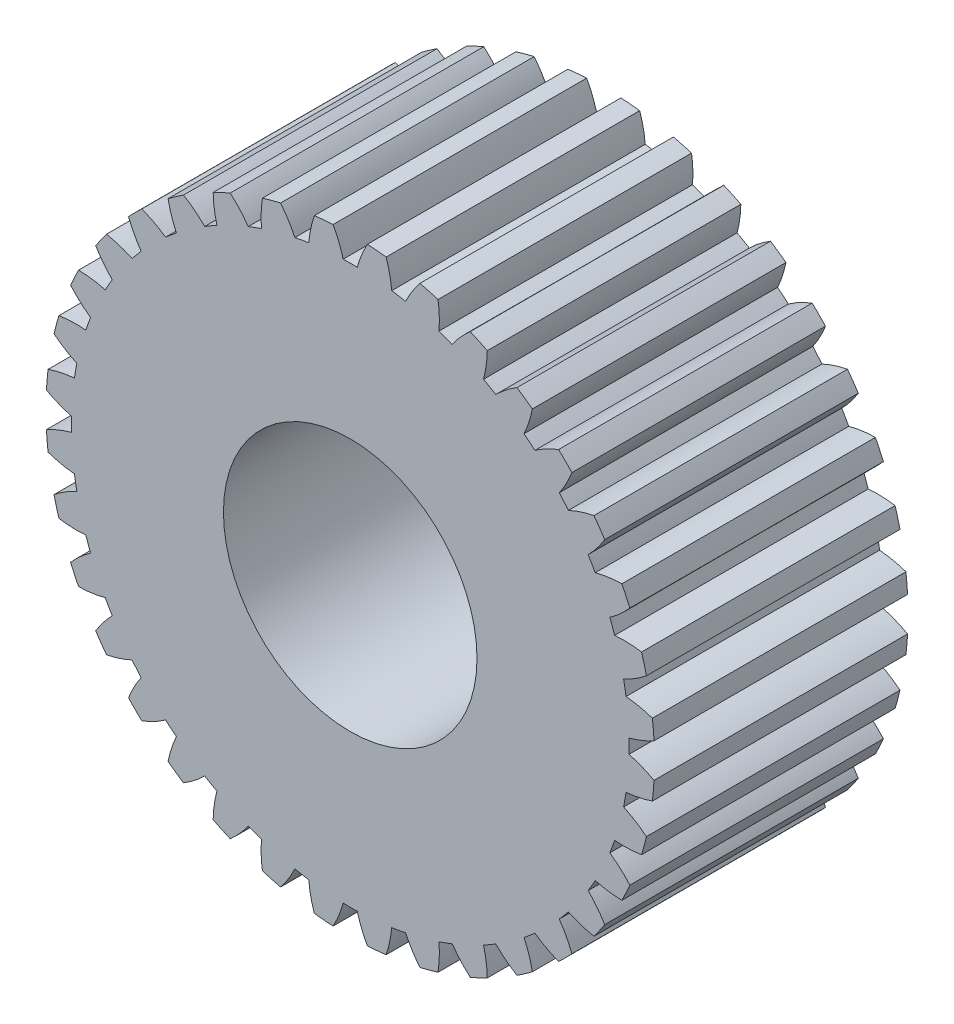
SolidWorks part; units mm, degrees
ref_plane "Front Plane" through (0, 0, 0) normal (0, 0, 1) x (1, 0, 0)
ref_plane "Top Plane" through (0, 0, 0) normal (0, 1, 0) x (1, 0, 0)
ref_plane "Right Plane" through (0, 0, 0) normal (1, 0, 0) x (0, 0, -1)
sketch "Sketch1" plane through (0, 0, 0) normal (0, 0, 1) x (1, 0, 0)
  circle A0 centre (0, 0) radius 5
  circle A1 centre (0, 0) radius 12
  dimension "D1" = 10
  dimension "D2" = 24
extrude "Boss-Extrude1" add sketch "Sketch1" along normal mid plane 10
sketch "Sketch2" plane through (0, 0, 0) normal (0, 0, 1) x (1, 0, 0)
  line L0 (0, 0) -> (0, 15.5125) construction
  line L1 (0, 0) -> (-1.3597, 15.5413) construction
  line L2 (0, 0) -> (1.3424, 15.3437) construction
  arc A0 (0.2777, 10.9965) -> (-0.2777, 10.9965) centre (0, 0) ccw
  circle A1 centre (0, 0) radius 12 construction
  arc A2 (0.6754, 11.981) -> (-0.6754, 11.981) centre (0, 0) ccw
  spline S0 degree 2 poles (-0.2777, 10.9965) (-0.4169, 11.5131) (-0.6754, 11.981) knots 0 0 0 1 1 1
  spline S1 degree 2 poles (0.2777, 10.9965) (0.4169, 11.5131) (0.6754, 11.981) knots 0 0 0 1 1 1
  point P6 (-0.6506, 11.9961)
  point P8 (-0.2777, 10.9965)
  point P9 (-0.6566, 11.982)
  point P10 (-0.7042, 11.9765)
  point P11 (-0.6754, 11.981)
  point P15 (-0.3973, 11.5581)
  point P16 (-0.2544, 10.9852)
  point P17 (-0.4577, 11.6034)
  point P18 (-0.7586, 11.976)
  point P19 (-0.4577, 11.5279)
  point P23 (0.7111, 11.9789)
  dimension "D3" = 22
  dimension "D1" = 5
  dimension "D2" = 5
extrude "Cut-Extrude1" cut sketch "Sketch2" against normal mid plane 10
pattern_circular "CirPattern1" count 36 over 360 about axis through (0, 0, 5) along (0, 0, -1) of "Cut-Extrude1"
